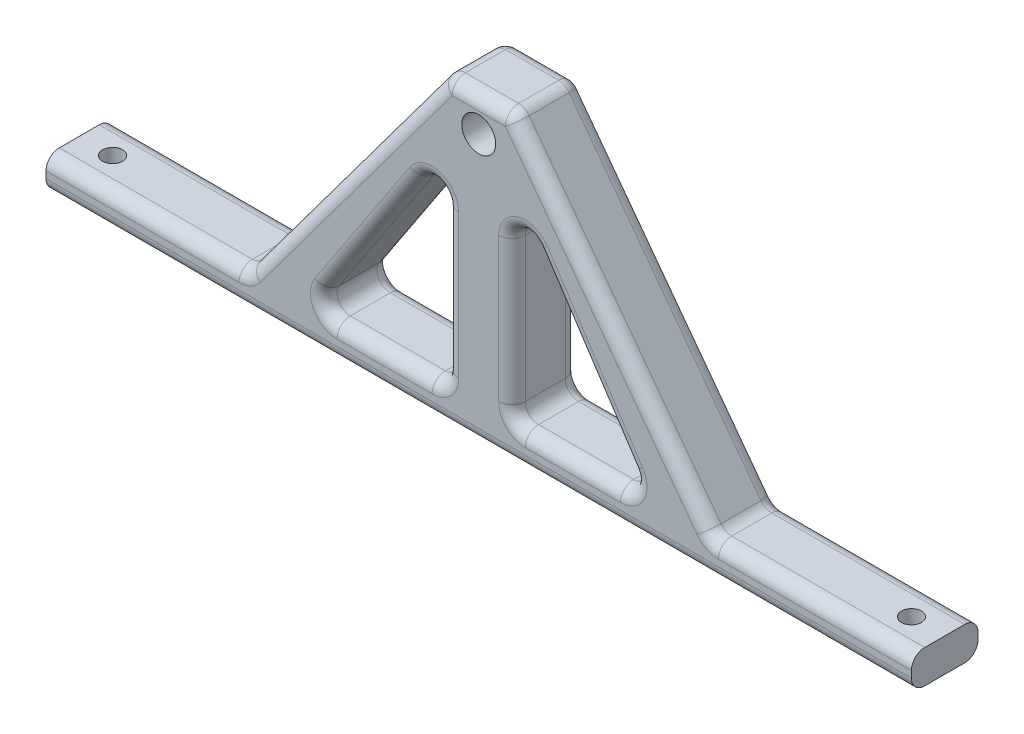
SolidWorks part; units mm, degrees
ref_plane "Front Plane" through (0, 0, 0) normal (0, 0, 1) x (1, 0, 0)
ref_plane "Top Plane" through (0, 0, 0) normal (0, 1, 0) x (1, 0, 0)
ref_plane "Right Plane" through (0, 0, 0) normal (1, 0, 0) x (0, 0, -1)
sketch "Sketch1" plane through (0, 0, 0) normal (0, 0, 1) x (1, 0, 0)
  line L0 (-21.861, 19.6011) -> (-11.861, 19.6011)
  line L1 (-11.861, 19.6011) -> (18.139, -20.6789)
  line L2 (18.139, -20.6789) -> (48.139, -20.6789)
  line L3 (48.139, -20.6789) -> (48.139, -25.6789)
  line L4 (48.139, -25.6789) -> (-81.861, -25.6789)
  line L5 (-81.861, -25.6789) -> (-81.861, -20.6789)
  line L6 (-81.861, -20.6789) -> (-51.861, -20.6789)
  line L7 (-51.861, -20.6789) -> (-21.861, 19.6011)
  line L8 (-41.861, -20.6789) -> (-21.861, 9.6011)
  line L9 (-21.861, 9.6011) -> (-21.861, -20.6789)
  line L10 (-21.861, -20.6789) -> (-41.861, -20.6789)
  line L11 (-11.861, 9.6011) -> (-11.861, -20.6789)
  line L12 (-11.861, -20.6789) -> (8.139, -20.6789)
  line L13 (8.139, -20.6789) -> (-11.861, 9.6011)
  circle A0 centre (-16.861, 14.6011) radius 2.55
  dimension "D4" = 5.1
  dimension "D5" = 5
  dimension "D6" = 5
  dimension "D1" = 10
  dimension "D2" = 5
  dimension "D3" = 5
  dimension "D7" = 40.28
  dimension "D8" = 30
  dimension "D9" = 30
  dimension "D10" = 30
  dimension "D11" = 30
  dimension "D12" = 5
  dimension "D13" = 10
  dimension "D14" = 10
  dimension "D15" = 10
  dimension "D16" = 10
  dimension "D17" = 10
extrude "Boss-Extrude1" add sketch "Sketch1" along normal blind 10
sketch "Sketch2" plane through (0, -20.6789, 0) normal (0, 1, 0) x (1, 0, 0)
  line L0 (48.139, -10) -> (48.139, 0) construction
  line L1 (-81.861, -10) -> (-81.861, 0) construction
  line L2 (-51.861, -10) -> (-81.861, -10) construction
  line L3 (48.139, -10) -> (18.139, -10) construction
  circle A0 centre (43.139, -5) radius 1.5
  circle A1 centre (-76.861, -5) radius 1.5
  dimension "D1" = 3
  dimension "D2" = 3
  dimension "D3" = 5
  dimension "D4" = 5
  dimension "D5" = 5
  dimension "D6" = 5
extrude "Cut-Extrude1" cut sketch "Sketch2" against normal blind 5
fillet "Fillet1" radius 2 10 edges at (-21.861, -20.6789, 5) (-21.861, 9.6011, 5) (-41.861, -20.6789, 5) (-11.861, -20.6789, 5) (-11.861, 9.6011, 5) (8.139, -20.6789, 5) (-51.861, -20.6789, 5) (18.139, -20.6789, 5) (-21.861, 19.6011, 5) (-11.861, 19.6011, 5)
fillet "Fillet2" radius 2 44 edges at (-22.4468, -20.0931, 0) (-31.0021, -20.6789, 0) (-39.9045, -19.6264, 0) (-32.6709, -6.7651, 0) (-23.2856, 4.8597, 0) (-10.4365, 4.8597, 0) (-1.0512, -6.7651, 0) (6.1824, -19.6264, 0) (-2.72, -20.6789, 0) (-11.2753, -20.0931, 0) (-23.2856, 4.8597, 10) (-21.861, -7.8673, 10) (-22.4468, -20.0931, 10) (-31.0021, -20.6789, 10) (-39.9045, -19.6264, 10) (-10.4365, 4.8597, 10) (-1.0512, -6.7651, 10) (6.1824, -19.6264, 10) (-2.72, -20.6789, 10) (-11.2753, -20.0931, 10) (33.641, -20.6789, 0) (18.2457, -20.4662, 0) (-67.3631, -20.6789, 0) (-51.9678, -20.4662, 0) (-36.861, -0.5389, 0) (-21.7543, 19.3885, 0) (-16.861, 19.6011, 0) (-11.9678, 19.3885, 0) (33.641, -20.6789, 10) (18.2457, -20.4662, 10) (3.139, -0.5389, 10) (-11.9678, 19.3885, 10) (-16.861, 19.6011, 10) (-21.7543, 19.3885, 10) (-67.3631, -20.6789, 10) (-51.9678, -20.4662, 10) (-21.861, -7.8673, 0) (-11.861, -7.8673, 0) (-32.6709, -6.7651, 10) (-11.861, -7.8673, 10) (-16.861, -25.6789, 0) (-16.861, -25.6789, 10) (3.139, -0.5389, 0) (-36.861, -0.5389, 10)
